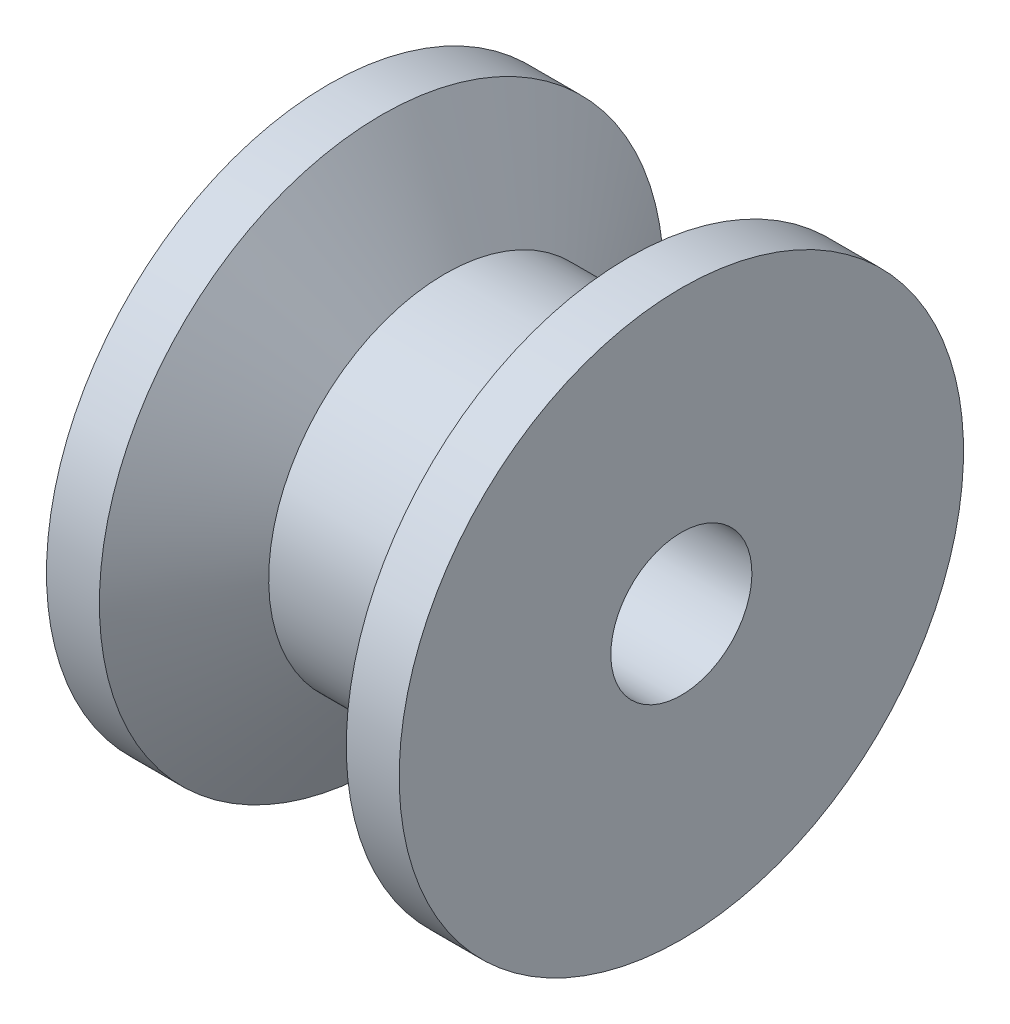
SolidWorks part; units mm, degrees
ref_plane "前视基准面" through (0, 0, 0) normal (0, 0, 1) x (1, 0, 0)
ref_plane "上视基准面" through (0, 0, 0) normal (0, 1, 0) x (1, 0, 0)
ref_plane "右视基准面" through (0, 0, 0) normal (1, 0, 0) x (0, 0, -1)
other "Configuration Table"
sketch "草图1" plane through (0, 0, 0) normal (0, 0, 1) x (1, 0, 0)
  line L0 (-114.203, 8.279) -> (-114.203, 88.279)
  line L1 (-114.203, 88.279) -> (-99.203, 88.279)
  line L2 (-99.203, 88.279) -> (-81.203, 58.279)
  line L3 (-81.203, 58.279) -> (-47.203, 58.279)
  line L4 (-47.203, 58.279) -> (-29.203, 88.279)
  line L5 (-29.203, 88.279) -> (-14.203, 88.279)
  line L6 (-14.203, 88.279) -> (-14.203, 8.279)
  line L7 (-14.203, 8.279) -> (-114.203, 8.279)
  dimension "D1" = 80
  dimension "D2" = 15
  dimension "D3" = 34
  dimension "D4" = 18
  dimension "D5" = 100
  dimension "D6" = 30
  dimension "D7" = 30
  dimension "D8" = 15
revolve "旋转1" add sketch "草图1" angle 360 about L7
sketch "草图2" plane through (-14.203, 0, 0) normal (1, 0, 0) x (0, 0, -1)
  circle A0 centre (0, 8.279) radius 20
  dimension "D1" = 40
extrude "切除-拉伸1" cut sketch "草图2" against normal through all
